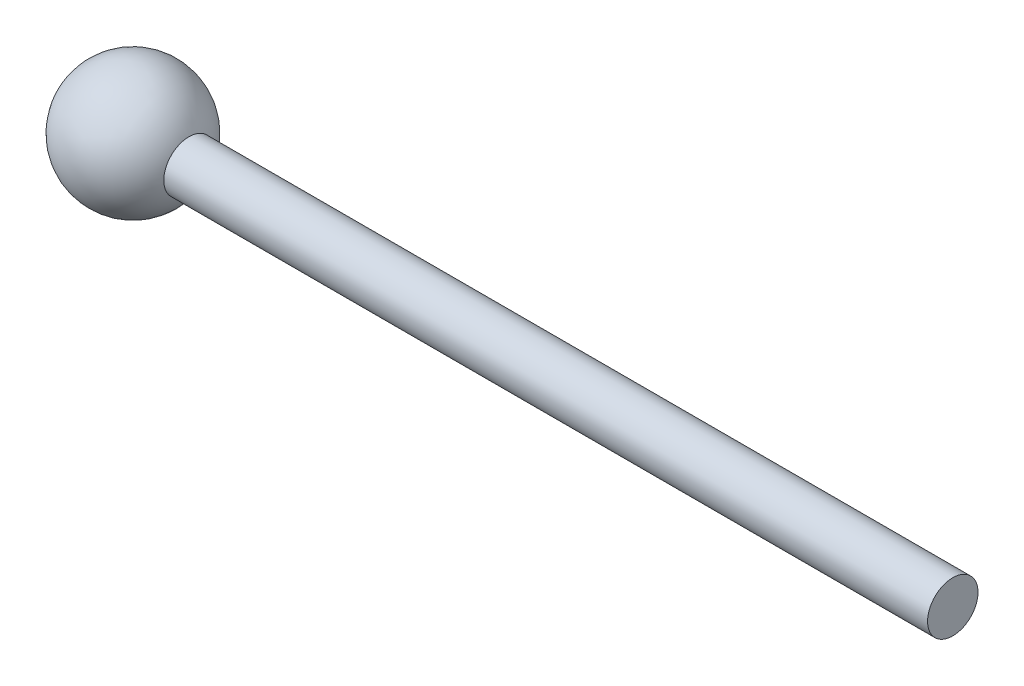
SolidWorks part; units mm, degrees
material "Plain Carbon Steel"
ref_plane "Front Plane" through (0, 0, 0) normal (0, 0, 1) x (1, 0, 0)
ref_plane "Top Plane" through (0, 0, 0) normal (0, 1, 0) x (1, 0, 0)
ref_plane "Right Plane" through (0, 0, 0) normal (1, 0, 0) x (0, 0, -1)
sketch "Sketch1" plane through (0, 0, 0) normal (0, 0, 1) x (1, 0, 0)
  line L0 (198.514, 0) -> (68.514, 0) construction
  line L1 (0, 0) -> (104.5713, 0) construction
  line L2 (198.514, 0) -> (198.514, -4)
  line L3 (198.514, -4) -> (77.4057, -4)
  line L4 (68.514, 0) -> (58.764, 0) construction
  line L5 (198.514, 0) -> (58.764, 0)
  arc A0 (58.764, 0) -> (77.4057, -4) centre (68.514, 0) ccw
  point P6 (68.514, 0)
  dimension "D1" = 19.5
  dimension "D2" = 4
  dimension "D3" = 130
revolve "Revolve1" add sketch "Sketch1" angle 360 about L5
